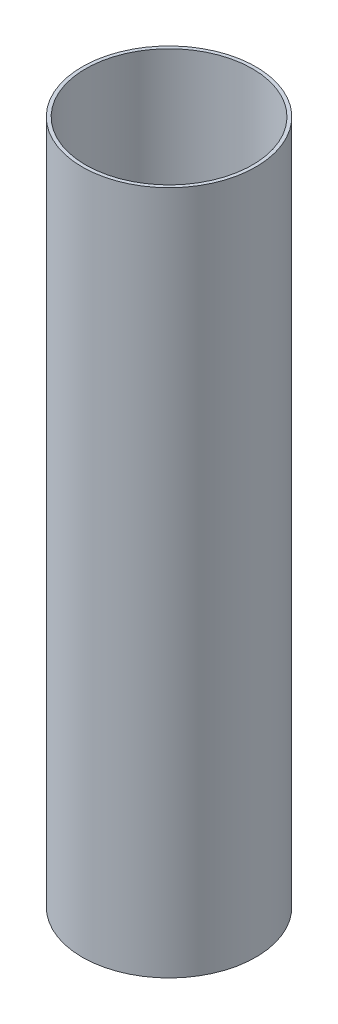
SolidWorks part; units mm, degrees
material "Hexcel AS4C (3000 Filaments)"
ref_plane "Front Plane" through (0, 0, 0) normal (0, 0, 1) x (1, 0, 0)
ref_plane "Top Plane" through (0, 0, 0) normal (0, 1, 0) x (1, 0, 0)
ref_plane "Right Plane" through (0, 0, 0) normal (1, 0, 0) x (0, 0, -1)
sketch "Sketch1" plane through (0, 0, 0) normal (0, 1, 0) x (1, 0, 0)
  circle A0 centre (0, 0) radius 49.53
  circle A1 centre (0, 0) radius 51.562
  dimension "D1" = 99.06
  dimension "D2" = 2.032
extrude "Boss-Extrude1" add sketch "Sketch1" along normal blind 406.4
equation "\"CF_OD_A\"= 4.015in"
equation "\"CF_ID_A\"= 3.904in"
equation "\"KF_ID_A\"= 4.015in ' Kevlar airframe ID"
equation "\"CF_OD_C\"= 3.894in ' VERIFY Coupler OD"
equation "\"CF_ID_C\"= 3.783in ' VERIFY Coupler ID"
equation "\"KF_WALL\"= 0.0625in"
equation "\"AF_01\"=10in"
equation "\"AF_02\"=16in"
equation "\"AF_03\"=in"
equation "\"B_CF_OD\"=6.17in"
equation "\"B_CF_ID\"=6in"
equation "\"B_CF_WT\"=0.085in"
equation "\"B_Fin_Root\"=18in"
equation "\"Al_WALL\"=0.08in"
equation "\"AL_ID_A\"=3.9in"
equation "\"D1@Sketch1\"=\"AL_ID_A\""
equation "\"D2@Sketch1\"=\"Al_WALL\""
equation "\"D1@Boss-Extrude1\"=\"AF_02\""
